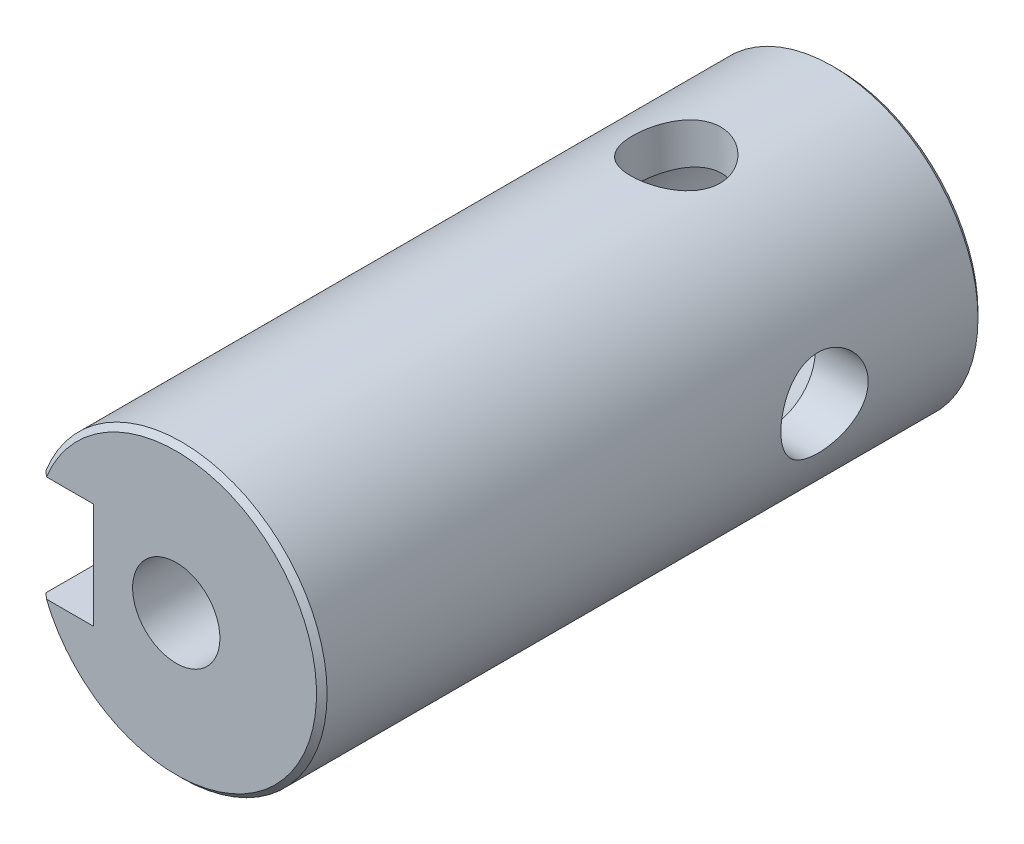
SolidWorks part; units mm, degrees
ref_plane "前视基准面" through (0, 0, 0) normal (0, 0, 1) x (1, 0, 0)
ref_plane "上视基准面" through (0, 0, 0) normal (0, 1, 0) x (1, 0, 0)
ref_plane "右视基准面" through (0, 0, 0) normal (1, 0, 0) x (0, 0, -1)
sketch "草图1" plane through (0, 0, 0) normal (0, 0, 1) x (1, 0, 0)
  circle A0 centre (0, 0) radius 5.5
extrude "凸台-拉伸1" add sketch "草图1" along normal blind 18
sketch "草图2" plane through (0, 0, 0) normal (0, 0, -1) x (-1, 0, 0)
  circle A0 centre (0, 0) radius 4
extrude "切除-拉伸1" cut sketch "草图2" against normal blind 18
sketch "草图3" plane through (0, 0, 0) normal (0, 0, -1) x (-1, 0, 0)
  line L1 (-3.5, 0) -> (-3.5, 2.5156)
  line L2 (-3.5, 2.5156) -> (-4.9444, -0.3036)
  line L3 (-4.9444, -0.3036) -> (-4.2222, -2.1803)
  line L4 (-4.2222, -2.1803) -> (-3.5, -2.1803)
  line L5 (-3.5, -2.1803) -> (-3.5, 0)
extrude "凸台-拉伸2" add sketch "草图3" against normal blind 18
sketch "草图5" plane through (0, 0, 0) normal (0, 0, -1) x (-1, 0, 0)
  line L6 (-4.5, 0) -> (-4.5, -1.5)
  line L7 (-4.5, -1.5) -> (-5.2915, -1.5)
  line L8 (-4.5, 0) -> (-4.5, 1.5)
  line L9 (-4.5, 1.5) -> (-5.2915, 1.5)
  line L10 (-5.2915, 1.5) -> (-6.68, 0.4007)
  line L11 (-6.68, 0.4007) -> (-5.2915, -1.5)
  circle A1 centre (0, 0) radius 5.5 construction
extrude "切除-拉伸3" cut sketch "草图5" against normal blind 6
sketch "草图6" plane through (0, 0, 6) normal (0, 0, -1) x (-1, 0, 0)
  line L0 (-5.2915, -1.5) -> (-4.2385, -1.6444)
  line L1 (-4.2385, -1.6444) -> (-3.814, 1.9303)
  line L2 (-3.814, 1.9303) -> (-5.2915, 1.5)
  arc A0 (-5.2915, 1.5) -> (-5.2915, -1.5) centre (0, 0) ccw
  arc A1 (-5.2915, 1.5) -> (-5.2915, -1.5) centre (0, 0) ccw construction
extrude "凸台-拉伸3" add sketch "草图6" along normal blind 6
sketch "草图11" plane through (0, 0, 18) normal (0, 0, 1) x (1, 0, 0)
  circle A0 centre (0, 0) radius 5.5
extrude "凸台-拉伸4" add sketch "草图11" along normal blind 7
sketch "草图15" plane through (0, 0, 18) normal (0, 0, -1) x (-1, 0, 0)
  circle A0 centre (0, 0) radius 5.5
extrude "凸台-拉伸5" add sketch "草图15" along normal blind 2
hole_wizard "M4 螺纹孔4" positions "3D草图4" profile "草图17" tap size "M4" standard "ISO" end condition up to next
sketch3d "3D草图4"
  line L0 (0, 0, 25) -> (0, 0, 0) construction
  point P0 (0, 0, 25)
sketch "草图17" plane through (0, 0, 25) normal (1, 0, 0) x (0, -1, 0)
  line L0 (0, 0) -> (0, 9)
  line L1 (0, 9) -> (1.65, 9)
  line L2 (1.65, 9) -> (1.65, 0)
  line L5 (1.65, 0) -> (0, 0)
  line L11 (0, -6.35) -> (0, 107.95) construction
  dimension "通孔螺纹孔钻头直径" = 3.3
  dimension "通孔螺纹孔钻头深度" = 9
cosmetic thread "孔螺蚊线4" parameters "D2"=4
sketch "草图19" plane through (0, 0, 25) normal (0, 0, 1) x (1, 0, 0)
  line L1 (-5.5, 0) -> (-5.5, -2)
  line L2 (-5.5, -2) -> (-3.5, -2)
  line L3 (-3.5, -2) -> (-3.5, 2)
  line L4 (-3.5, 2) -> (-5.5, 2)
  line L5 (-5.5, 2) -> (-5.5, 0)
  circle A0 centre (0, 0) radius 5.5 construction
extrude "切除-拉伸8" cut sketch "草图19" against normal blind 8
sketch "草图20" plane through (0, 0, 25) normal (0, 0, 1) x (1, 0, 0)
  line L0 (-3.5, -2) -> (-3.12, -2)
  line L1 (-3.12, -2) -> (-3.12, 2)
  line L2 (-3.12, 2) -> (-3.5, 2)
  line L3 (-3.5, 2) -> (-3.5, -2)
extrude "切除-拉伸9" cut sketch "草图20" against normal blind 8
sketch "草图31" plane through (3.5, 0, 0) normal (-1, 0, 0) x (0, 0, 1)
  line L0 (0, 0) -> (6, 0)
  line L1 (0, -1.9365) -> (0, 1.9365) construction
hole_wizard "M4 螺纹孔9" positions "3D草图10" profile "草图32" tap size "M4" standard "ISO"
sketch3d "3D草图10"
  point P0 (3.5, 0, 6)
sketch "草图32" plane through (3.5, 0, 6) normal (0, 1, 0) x (0, 0, 1)
  line L0 (0, 0) -> (0, 2)
  line L1 (0, 2) -> (1.65, 2)
  line L2 (1.65, 2) -> (1.65, 0)
  line L5 (1.65, 0) -> (0, 0)
  line L11 (0, -6.35) -> (0, 107.95) construction
  dimension "通孔螺纹孔钻头直径" = 3.3
  dimension "通孔螺纹孔钻头深度" = 2
cosmetic thread "孔螺蚊线9" parameters "D2"=4
hole_wizard "M4 螺纹孔10" positions "3D草图15" profile "草图39" tap size "M4" standard "ISO"
sketch3d "3D草图15"
  point P0 (-0.1127, 3.9984, 5.9528)
sketch "草图39" plane through (-0.1127, 3.9984, 5.9528) normal (0, 0, 1) x (0.9996, 0.0282, 0)
  line L0 (0, 0) -> (0, 1.5)
  line L1 (0, 1.5) -> (1.65, 1.5)
  line L2 (1.65, 1.5) -> (1.65, 0)
  line L5 (1.65, 0) -> (0, 0)
  line L11 (0, -6.35) -> (0, 107.95) construction
  dimension "通孔螺纹孔钻头直径" = 3.3
  dimension "通孔螺纹孔钻头深度" = 1.5
cosmetic thread "孔螺蚊线10" parameters "D2"=4
chamfer "倒角2" distance 0.2 angle 45 1 edges at (5.5, 0, 25)
chamfer "倒角3" distance 0.2 angle 45 1 edges at (5.5, 0, 0)
